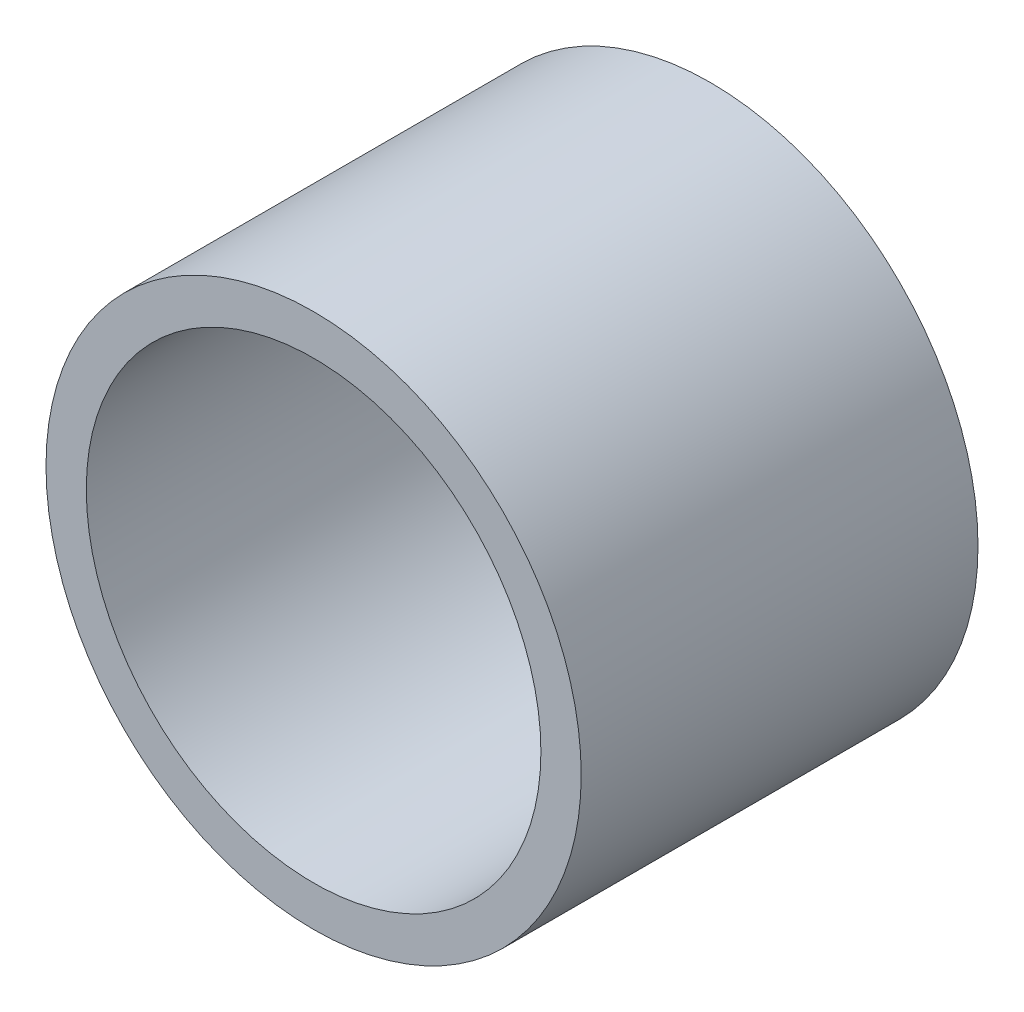
SolidWorks part; units mm, degrees
material "ABS"
ref_plane "Front Plane" through (0, 0, 0) normal (0, 0, 1) x (1, 0, 0)
ref_plane "Top Plane" through (0, 0, 0) normal (0, 1, 0) x (1, 0, 0)
ref_plane "Right Plane" through (0, 0, 0) normal (1, 0, 0) x (0, 0, -1)
sketch "Sketch1" plane through (0, 0, 0) normal (0, 0, 1) x (1, 0, 0)
  circle A0 centre (0, 0) radius 32.375
  circle A1 centre (0, 0) radius 27.5
  dimension "D1" = 64.75
  dimension "D2" = 55
extrude "Boss-Extrude1" add sketch "Sketch1" along normal blind 48.006
